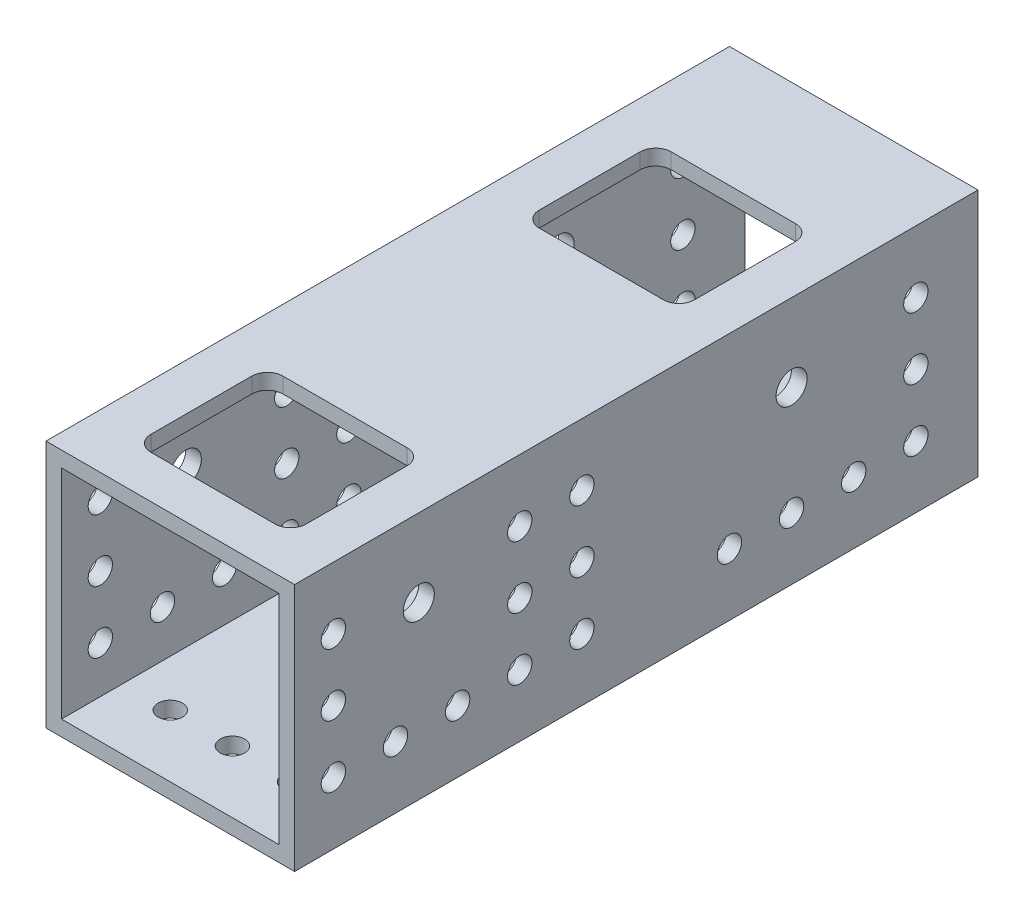
SolidWorks part; units mm, degrees
material "6061-T6 (SS)"
ref_plane "Front Plane" through (0, 0, 0) normal (0, 0, 1) x (1, 0, 0)
ref_plane "Top Plane" through (0, 0, 0) normal (0, 1, 0) x (1, 0, 0)
ref_plane "Right Plane" through (0, 0, 0) normal (1, 0, 0) x (0, 0, -1)
sketch "Sketch1" plane through (0, 0, 0) normal (0, 0, 1) x (1, 0, 0)
  line L1 (-25.4, -25.4) -> (25.4, -25.4)
  line L2 (-25.4, -25.4) -> (-25.4, 25.4)
  line L3 (-25.4, 25.4) -> (25.4, 25.4)
  line L4 (25.4, -25.4) -> (25.4, 25.4)
  line L5 (-25.4, -25.4) -> (25.4, 25.4) construction
  line L6 (-25.4, 25.4) -> (25.4, -25.4) construction
  point P0 (0, 0)
  dimension "D1" = 50.8
  dimension "D2" = 50.8
extrude "Boss-Extrude1" add sketch "Sketch1" along normal mid plane 139.7
shell "Shell1" thickness 3.175
sketch "Sketch2" plane through (0, 0, 0) normal (0, 1, 0) x (1, 0, 0)
  line L0 (25.4, 69.85) -> (-25.4, 69.85) construction
  line L1 (15.875, 45.2437) -> (-15.875, 45.2437)
  line L2 (15.875, 45.2437) -> (15.875, 18.2563)
  line L3 (15.875, 18.2563) -> (-15.875, 18.2563)
  line L4 (-15.875, 45.2437) -> (-15.875, 18.2563)
  line L5 (25.4, -69.85) -> (-25.4, -69.85) construction
  line L7 (15.875, -34.1313) -> (-15.875, -34.1313)
  line L8 (15.875, -34.1313) -> (15.875, -61.1187)
  line L9 (15.875, -61.1187) -> (-15.875, -61.1187)
  line L10 (-15.875, -34.1313) -> (-15.875, -61.1187)
  point P4 (0, 45.2437)
  point P7 (0, 69.85)
  point P9 (15.875, 31.75)
  point P15 (0, -69.85)
  point P16 (0, -61.1187)
  point P17 (-15.875, -47.625)
  dimension "D1" = 31.75
  dimension "D2" = 26.9875
  dimension "D3" = 101.6
  dimension "D4" = 22.225
extrude "Cut-Extrude1" cut sketch "Sketch2" along normal through all
fillet "Fillet1" radius 3.175 4 edges at (15.875, 23.8125, -45.2437) (-15.875, 23.8125, -45.2437) (-15.875, 23.8125, -18.2563) (15.875, 23.8125, -18.2563)
sketch "Sketch3" plane through (0, 0, 0) normal (1, 0, 0) x (0, 0, -1)
  line L1 (-69.85, 25.4) -> (-69.85, -25.4) construction
  line L2 (-69.85, 25.4) -> (69.85, 25.4) construction
  circle A0 centre (31.75, 9.525) radius 3.175
  circle A1 centre (-44.45, 9.525) radius 3.175
  dimension "D1" = 6.35
  dimension "D2" = 25.4
  dimension "D3" = 76.2
  dimension "D4" = 15.875
extrude "Cut-Extrude2" cut sketch "Sketch3" against normal through all both and the other way through all
sketch "Sketch4" plane through (0, 0, 0) normal (1, 0, 0) x (0, 0, -1)
  line L0 (-69.85, 25.4) -> (69.85, 25.4) construction
  line L1 (69.85, 25.4) -> (69.85, -25.4) construction
  line L2 (-69.85, 25.4) -> (-69.85, -25.4) construction
  circle A0 centre (57.15, 12.7) radius 2.4892
  circle A1 centre (44.45, 12.7) radius 2.4892 construction
  circle A2 centre (31.75, 12.7) radius 2.4892 construction
  circle A3 centre (19.05, 12.7) radius 2.4892 construction
  circle A10 centre (44.45, 0) radius 2.4892 construction
  circle A11 centre (31.75, 0) radius 2.4892 construction
  circle A12 centre (19.05, 0) radius 2.4892 construction
  circle A19 centre (44.45, -12.7) radius 2.4892
  circle A20 centre (31.75, -12.7) radius 2.4892
  circle A21 centre (19.05, -12.7) radius 2.4892
  circle A28 centre (57.15, 0) radius 2.4892
  circle A29 centre (57.15, -12.7) radius 2.4892
  circle A30 centre (-61.9125, 12.7) radius 2.4892
  circle A31 centre (-49.2125, 12.7) radius 2.4892 construction
  circle A32 centre (-36.5125, 12.7) radius 2.4892 construction
  circle A33 centre (-23.8125, 12.7) radius 2.4892
  circle A34 centre (-11.1125, 12.7) radius 2.4892
  circle A35 centre (1.5875, 12.7) radius 2.4892 construction
  circle A36 centre (-49.2125, 0) radius 2.4892 construction
  circle A37 centre (-36.5125, 0) radius 2.4892 construction
  circle A38 centre (-23.8125, 0) radius 2.4892
  circle A39 centre (-11.1125, 0) radius 2.4892
  circle A40 centre (1.5875, 0) radius 2.4892 construction
  circle A41 centre (-49.2125, -12.7) radius 2.4892
  circle A42 centre (-36.5125, -12.7) radius 2.4892
  circle A43 centre (-23.8125, -12.7) radius 2.4892
  circle A44 centre (-11.1125, -12.7) radius 2.4892
  circle A45 centre (1.5875, -12.7) radius 2.4892 construction
  circle A46 centre (-61.9125, 0) radius 2.4892
  circle A47 centre (-61.9125, -12.7) radius 2.4892
  dimension "D1" = 4.9784
  dimension "D3" = 12.7
  dimension "D8" = 4.9784
  dimension "D9" = 7.9375
  dimension "D14" = 12.7
  dimension "D2" = 12.7
  dimension "D6" = 12.7
  dimension "D7" = 12.7
  dimension "D10" = 12.7
  dimension "D13" = 12.7
  dimension "D4" = 4
  dimension "D5" = 3
  dimension "D11" = 6
  dimension "D12" = 3
extrude "Cut-Extrude3" cut sketch "Sketch4" against normal through all both and the other way through all
sketch "Sketch5" plane through (0, 0, 0) normal (0, 1, 0) x (1, 0, 0)
  line L1 (25.4, -69.85) -> (-25.4, -69.85) construction
  line L2 (-25.4, -69.85) -> (-25.4, 69.85) construction
  circle A0 centre (-12.7, -57.15) radius 2.4892
  circle A1 centre (0, -57.15) radius 2.4892
  circle A2 centre (12.7, -57.15) radius 2.4892
  dimension "D1" = 4.9784
  dimension "D3" = 12.7
  dimension "D2" = 12.7
  dimension "D5" = 12.7
  dimension "D4" = 3
extrude "Cut-Extrude4" cut sketch "Sketch5" against normal through all and the other way through all
fillet "Fillet2" radius 3.175 4 edges at (-15.875, 23.8125, 34.1313) (-15.875, 23.8125, 61.1187) (15.875, 23.8125, 61.1187) (15.875, 23.8125, 34.1313)
